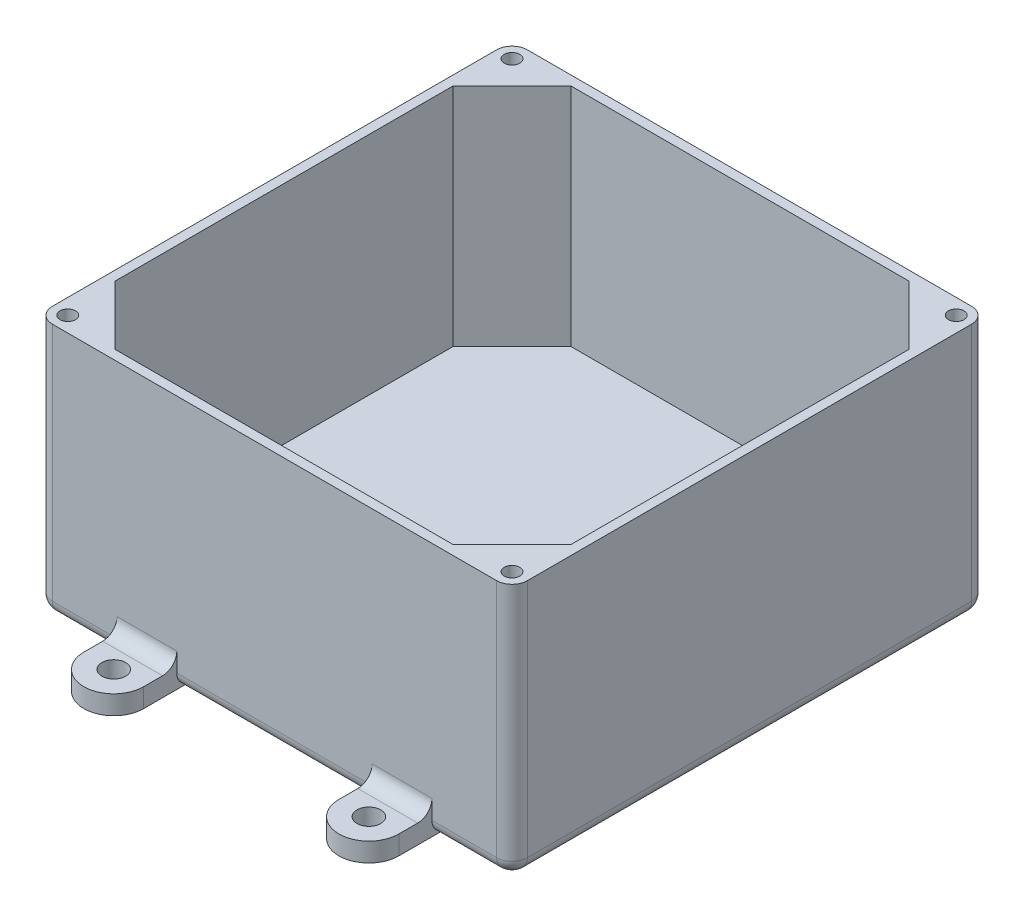
SolidWorks part; units mm, degrees
ref_plane "Front Plane" through (0, 0, 0) normal (0, 0, 1) x (1, 0, 0)
ref_plane "Top Plane" through (0, 0, 0) normal (0, 1, 0) x (1, 0, 0)
ref_plane "Right Plane" through (0, 0, 0) normal (1, 0, 0) x (0, 0, -1)
sketch "Sketch1" plane through (0, 0, 0) normal (0, 1, 0) x (1, 0, 0)
  line L1 (-50, -50) -> (50, -50)
  line L2 (-50, -50) -> (-50, 50)
  line L3 (-50, 50) -> (50, 50)
  line L4 (50, -50) -> (50, 50)
  line L5 (-50, -50) -> (50, 50) construction
  line L6 (-50, 50) -> (50, -50) construction
  point P0 (0, 0)
  dimension "D1" = 100
  dimension "D2" = 100
extrude "Boss-Extrude1" add sketch "Sketch1" along normal blind 53.5
sketch "Sketch2" plane through (0, 0, 0) normal (0, -1, 0) x (1, 0, 0)
  line L0 (0, 0) -> (0, -50)
  line L1 (50, -50) -> (-50, -50) construction
  line L2 (-20.55, -50) -> (20.55, -50)
  line L3 (-20.55, -50) -> (-20.55, -56.9738)
  line L4 (-33.15, -50) -> (-33.15, -56.9738)
  line L6 (-33.15, -50) -> (-33.15, -46.9276)
  line L7 (-33.15, -46.9276) -> (-20.55, -46.9276)
  line L8 (-20.55, -46.9276) -> (-20.55, -50)
  line L9 (20.55, -50) -> (20.55, -56.9738)
  line L10 (33.15, -50) -> (33.15, -56.9738)
  line L11 (33.15, -50) -> (33.15, -46.9276)
  line L12 (33.15, -46.9276) -> (20.55, -46.9276)
  line L13 (20.55, -46.9276) -> (20.55, -50)
  line L14 (-18.3596, 0) -> (18.3596, 0)
  line L15 (20.55, 46.9276) -> (20.55, 50)
  line L16 (33.15, 46.9276) -> (20.55, 46.9276)
  line L17 (33.15, 50) -> (33.15, 46.9276)
  line L18 (33.15, 50) -> (33.15, 56.9738)
  line L19 (20.55, 50) -> (20.55, 56.9738)
  line L20 (-20.55, 50) -> (-20.55, 56.9738)
  line L21 (-33.15, 50) -> (-33.15, 56.9738)
  line L22 (-33.15, 50) -> (-33.15, 46.9276)
  line L23 (-33.15, 46.9276) -> (-20.55, 46.9276)
  line L24 (-20.55, 46.9276) -> (-20.55, 50)
  arc A0 (-33.15, -56.9738) -> (-20.55, -56.9738) centre (-26.85, -56.9738) ccw
  circle A1 centre (-26.85, -56.9738) radius 2.5
  circle A2 centre (26.85, -56.9738) radius 2.5
  arc A3 (33.15, -56.9738) -> (20.55, -56.9738) centre (26.85, -56.9738) cw
  circle A4 centre (26.85, 56.9738) radius 2.5
  arc A5 (33.15, 56.9738) -> (20.55, 56.9738) centre (26.85, 56.9738) ccw
  circle A6 centre (-26.85, 56.9738) radius 2.5
  arc A7 (-33.15, 56.9738) -> (-20.55, 56.9738) centre (-26.85, 56.9738) cw
  point P24 (0, 0)
  line M18 (50, 50) -> (-50, 50)
  line M20 (-50, -50) -> (50, -50)
  dimension "D3" = 12.6
  dimension "D2" = 20.55
extrude "Boss-Extrude2" add sketch "Sketch2" against normal blind 4 contours A3 L10 L9 A2 M20 | L4 A0 L3 A1 M20 | L23 L24 L22 M18 | A7 L21 L20 A6 M18 | L18 A5 L19 A4 M18 | L17 L15 L16 M18 | L12 L13 L11 M20 | L8 L7 L6 M20
sketch "Sketch3" plane through (0, 53.5, 0) normal (0, 1, 0) x (1, 0, 0)
  line L0 (-35.565, 48) -> (35.565, 48)
  line L1 (-48, -48) -> (48, -48)
  line L2 (-48, -48) -> (-48, 48)
  line L3 (-48, 48) -> (48, 48)
  line L4 (48, -48) -> (48, 48)
  line L5 (-48, -48) -> (48, 48) construction
  line L6 (-48, 48) -> (48, -48) construction
  line L7 (-48, -35.565) -> (-48, 35.565)
  line L8 (-48, 35.565) -> (-35.565, 48)
  line L9 (0, 0) -> (0, -12.9219)
  line L10 (0, -29.425) -> (0, 29.425) construction
  line L11 (0, 0) -> (14.2301, 0)
  line L12 (-29.425, 0) -> (29.425, 0) construction
  line L13 (-48, -35.565) -> (-35.565, -48)
  line L14 (48, -35.565) -> (35.565, -48)
  line L15 (48, 35.565) -> (35.565, 48)
  point P0 (0, 0)
  point P9 (0, 48)
  point P12 (-48, 0)
  point P17 (0, 0)
  dimension "D1" = 11.6213
  dimension "D2" = 96
  dimension "D3" = 71.13
extrude "Cut-Extrude1" cut sketch "Sketch3" against normal blind 47.5
fillet "Fillet1" radius 3.25 4 edges at (50, 26.75, 50) (-50, 26.75, 50) (-50, 26.75, -50) (50, 26.75, -50)
fillet "Fillet2" radius 3 4 edges at (26.85, 4, -50) (-26.85, 4, -50) (-26.85, 4, 50) (26.85, 4, 50)
sketch "Sketch4" plane through (0, 53.5, 0) normal (0, 1, 0) x (1, 0, 0)
  line L0 (-49.0481, 49.0481) -> (-46.75, 46.75)
  line L1 (0, 0) -> (0, 11.199)
  line L2 (0, -29.425) -> (0, 29.425) construction
  line L3 (0, 0) -> (-16.0806, 0)
  line L4 (-29.425, 0) -> (29.425, 0) construction
  arc A0 (-46.75, 50) -> (-50, 46.75) centre (-46.75, 46.75) ccw construction
  circle A1 centre (-46.75, 46.75) radius 1.625
  circle A2 centre (46.75, 46.75) radius 1.625
  circle A3 centre (46.75, -46.75) radius 1.625
  circle A4 centre (-46.75, -46.75) radius 1.625
extrude "Cut-Extrude2" cut sketch "Sketch4" against normal blind 14
fillet "Fillet3" radius 3 12 edges at (39.95, 0, -50) (49.0481, 0, -49.0481) (50, 0, 0) (49.0481, 0, 49.0481) (-39.95, 0, -50) (-49.0481, 0, -49.0481) (-50, 0, 0) (-49.0481, 0, 49.0481) (0, 0, -50) (39.95, 0, 50) (-39.95, 0, 50) (0, 0, 50)
